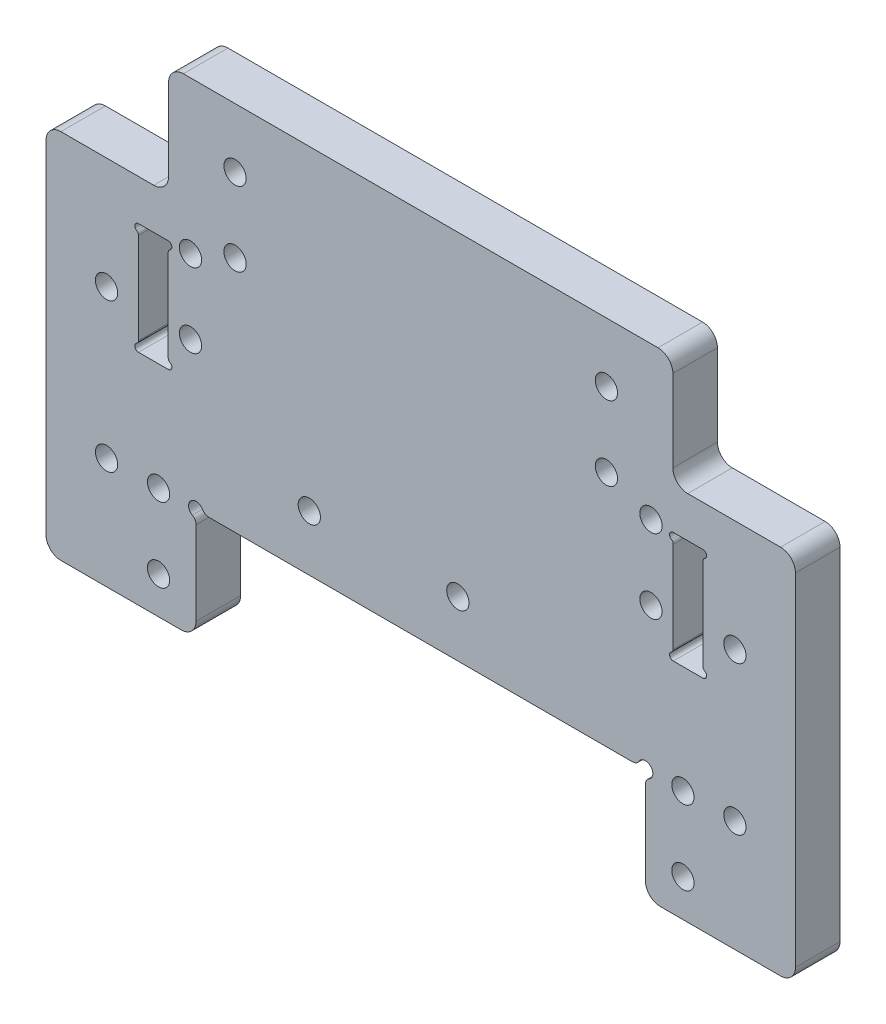
SolidWorks part; units mm, degrees
material "Thornel Mat VMA"
ref_plane "前视基准面" through (0, 0, 0) normal (0, 0, 1) x (1, 0, 0)
ref_plane "上视基准面" through (0, 0, 0) normal (0, 1, 0) x (1, 0, 0)
ref_plane "右视基准面" through (0, 0, 0) normal (1, 0, 0) x (0, 0, -1)
other "Configuration Table"
sketch "草图1" plane through (0, 0, 0) normal (0, 0, 1) x (1, 0, 0)
  line L0 (0, 0) -> (0, 15) construction
  line L1 (-35.3, -5) -> (35.3, -5) construction
  line L2 (-35.3, -5) -> (-35.3, 5) construction
  line L3 (-35.3, 5) -> (35.3, 5) construction
  line L4 (35.3, -5) -> (35.3, 5) construction
  line L5 (-35.3, -5) -> (35.3, 5) construction
  line L6 (-35.3, 5) -> (35.3, -5) construction
  line L7 (-42.3, 25) -> (-42.3, 5) construction
  line L8 (-42.3, 25) -> (42.3, 25) construction
  line L9 (-42.3, 25) -> (-42.3, 5) construction
  line L10 (-42.3, 5) -> (42.3, 5) construction
  line L11 (42.3, 25) -> (42.3, 5) construction
  line L12 (-42.3, 25) -> (42.3, 5) construction
  line L13 (-42.3, 5) -> (42.3, 25) construction
  line L14 (-35.3, -5) -> (-35.3, 5) construction
  line L16 (-50.45, 30) -> (50.45, 30)
  line L17 (-50.45, 30) -> (-50.45, -10)
  line L18 (-50.45, -10) -> (50.45, -10)
  line L19 (50.45, 30) -> (50.45, -10)
  line L20 (-50.45, 30) -> (50.45, -10) construction
  line L21 (-50.45, -10) -> (50.45, 30) construction
  circle A0 centre (42.3, 25) radius 1.5
  circle A1 centre (42.3, 5) radius 1.5
  circle A2 centre (35.3, 5) radius 1.5
  circle A3 centre (35.3, -5) radius 1.5
  circle A4 centre (-35.3, -5) radius 1.5
  circle A5 centre (-35.3, 5) radius 1.5
  circle A6 centre (-42.3, 5) radius 1.5
  circle A7 centre (-42.3, 25) radius 1.5
  point P0 (0, 0)
  point P20 (0, 10)
  dimension "D6" = 15
  dimension "D7" = 3
  dimension "D1" = 10
  dimension "D2" = 20
  dimension "D3" = 70.6
  dimension "D4" = 84.6
  dimension "D5" = 5
  dimension "D8" = 100.9
  dimension "D9" = 10
extrude "凸台-拉伸1" add sketch "草图1" along normal blind 6
sketch "草图6" plane through (0, 0, 6) normal (0, 0, 1) x (1, 0, 0)
  line L0 (0, 0) -> (0, 35) construction
  line L2 (-50.45, 40) -> (50.45, 40)
  line L3 (-50.45, 40) -> (-50.45, 30)
  line L4 (-50.45, 30) -> (50.45, 30)
  line L5 (50.45, 40) -> (50.45, 30)
  line L6 (-50.45, 40) -> (50.45, 30) construction
  line L7 (-50.45, 30) -> (50.45, 40) construction
  dimension "D1" = 10
extrude "凸台-拉伸2" add sketch "草图6" against normal up to surface (6 mm away) up to face at (0, 10, 0)
sketch "草图2" plane through (0, 0, 6) normal (0, 0, 1) x (1, 0, 0)
  line L0 (0, 0) -> (0, -2.5) construction
  line L1 (-50.45, -10) -> (50.45, -10) construction
  line L2 (-30.25, 5) -> (30.25, 5)
  line L3 (-30.25, 5) -> (-30.25, -10)
  line L4 (-30.25, -10) -> (30.25, -10)
  line L5 (30.25, 5) -> (30.25, -10)
  line L6 (-30.25, 5) -> (30.25, -10) construction
  line L7 (-30.25, -10) -> (30.25, 5) construction
  dimension "D1" = 60.5
  dimension "D2" = 15
extrude "切除-拉伸1" cut sketch "草图2" against normal blind 10
sketch "草图3" plane through (0, 0, 6) normal (0, 0, 1) x (1, 0, 0)
  circle A0 centre (-30.25, 5) radius 1
  circle A1 centre (30.25, 5) radius 1
  dimension "D1" = 2
extrude "切除-拉伸2" cut sketch "草图3" against normal blind 10
sketch "草图4" plane through (0, 0, 6) normal (0, 0, 1) x (1, 0, 0)
  line L0 (0, 0) -> (0, 29.5) construction
  line L2 (-31, 34.5) -> (31, 34.5) construction
  line L3 (-31, 34.5) -> (-31, 24.5) construction
  line L4 (-31, 24.5) -> (31, 24.5) construction
  line L5 (31, 34.5) -> (31, 24.5) construction
  line L6 (-31, 34.5) -> (31, 24.5) construction
  line L7 (-31, 24.5) -> (31, 34.5) construction
  circle A0 centre (31, 34.5) radius 1.5
  circle A1 centre (31, 24.5) radius 1.5
  circle A2 centre (-31, 24.5) radius 1.5
  circle A3 centre (-31, 34.5) radius 1.5
  dimension "D2" = 3
  dimension "D1" = 10
  dimension "D3" = 62
  dimension "D4" = 29.5
extrude "切除-拉伸3" cut sketch "草图4" against normal blind 10
sketch "草图5" plane through (0, 0, 6) normal (0, 0, 1) x (1, 0, 0)
  line L0 (0, 0) -> (0, 12.5) construction
  line L1 (0, 12.5) -> (-15, 12.5) construction
  line L2 (29.25, 5) -> (-29.25, 5) construction
  line L3 (0, 12.5) -> (5, 12.5) construction
  circle A0 centre (-15, 12.5) radius 1.5
  circle A2 centre (5, 12.5) radius 1.5
  dimension "D1" = 3
  dimension "D4" = 5
  dimension "D2" = 15
  dimension "D3" = 7.5
extrude "切除-拉伸4" cut sketch "草图5" against normal blind 10
sketch "草图7" plane through (0, 0, 6) normal (0, 0, 1) x (1, 0, 0)
  line L0 (0, 0) -> (0, 27) construction
  line L1 (0, 27) -> (36, 27) construction
  line L2 (50.45, 40) -> (-50.45, 40) construction
  line L3 (34, 19.5) -> (38, 19.5)
  line L4 (34, 19.5) -> (34, 34.5)
  line L5 (34, 34.5) -> (38, 34.5)
  line L6 (38, 19.5) -> (38, 34.5)
  line L7 (34, 19.5) -> (38, 34.5) construction
  line L8 (34, 34.5) -> (38, 19.5) construction
  line L10 (-34, 34.5) -> (-38, 19.5) construction
  line L11 (-34, 19.5) -> (-38, 34.5) construction
  line L12 (-38, 19.5) -> (-38, 34.5)
  line L13 (-34, 34.5) -> (-38, 34.5)
  line L14 (-34, 19.5) -> (-34, 34.5)
  line L15 (-34, 19.5) -> (-38, 19.5)
  circle A0 centre (31, 24.5) radius 1.5 construction
  dimension "D1" = 3
  dimension "D2" = 4
  dimension "D3" = 5.5
  dimension "D4" = 15
extrude "切除-拉伸5" cut sketch "草图7" against normal up to surface (6 mm away) up to face at (-13.5, 12.5, 0)
sketch "草图8" plane through (0, 0, 6) normal (0, 0, 1) x (1, 0, 0)
  line L0 (0, 0) -> (0, 45.2121) construction
  line L1 (-34, 19.5) -> (-34, 34.5) construction
  line L2 (-38, 34.5) -> (-38, 19.5) construction
  line L3 (-38, 34.5) -> (-38, 19.5)
  line L4 (-34, 19.5) -> (-34, 34.5)
  line L5 (34, 19.5) -> (34, 34.5)
  line L6 (38, 34.5) -> (38, 19.5)
  arc A0 (-34, 34.5) -> (-34, 33.5) centre (-34, 34) cw
  arc A1 (-38, 34.5) -> (-38, 33.5) centre (-38, 34) ccw
  arc A2 (-38, 19.5) -> (-38, 20.5) centre (-38, 20) cw
  arc A3 (-34, 19.5) -> (-34, 20.5) centre (-34, 20) ccw
  arc A4 (34, 19.5) -> (34, 20.5) centre (34, 20) cw
  arc A5 (38, 19.5) -> (38, 20.5) centre (38, 20) ccw
  arc A6 (38, 34.5) -> (38, 33.5) centre (38, 34) cw
  arc A7 (34, 34.5) -> (34, 33.5) centre (34, 34) ccw
  line M1 (38, 34.5) -> (38, 19.5)
  line M3 (34, 19.5) -> (34, 34.5)
  line M5 (-34, 34.5) -> (-34, 19.5)
  line M7 (-38, 19.5) -> (-38, 34.5)
  dimension "D1" = 0.5
extrude "切除-拉伸6" cut sketch "草图8" against normal up to surface (6 mm away) contours L3 A1 | A0 M5 | A2 M7 | A3 M5 | A6 M1 | A7 M3 | A4 M3 | L6 A5 up to face at (36, 27, 0)
fillet "圆角1" radius 0.5 8 edges at (38, 20.5, 3) (34, 20.5, 3) (34, 33.5, 3) (38, 33.5, 3) (-38, 20.5, 3) (-38, 33.5, 3) (-34, 33.5, 3) (-34, 20.5, 3)
fillet "圆角2" radius 1 4 edges at (30.25, 4, 3) (29.25, 5, 3) (-30.25, 4, 3) (-29.25, 5, 3)
sketch "草图9" plane through (0, 0, 6) normal (0, 0, 1) x (1, 0, 0)
  line L0 (0, 47.5) -> (0, 0) construction
  line L1 (-50.45, 55) -> (50.45, 55)
  line L2 (-50.45, 55) -> (-50.45, 40)
  line L3 (-50.45, 40) -> (50.45, 40)
  line L4 (50.45, 55) -> (50.45, 40)
  line L5 (-50.45, 55) -> (50.45, 40) construction
  line L6 (-50.45, 40) -> (50.45, 55) construction
  point P0 (0, 47.5)
  dimension "D1" = 15
extrude "凸台-拉伸3" add sketch "草图9" against normal up to surface (6 mm away) up to face at (-36, 27, 0)
sketch "草图10" plane through (0, 0, 6) normal (0, 0, 1) x (1, 0, 0)
  line L0 (0, 0) -> (0, 57.8919) construction
  line L1 (-33.95, 55) -> (-33.95, 40)
  line L2 (50.45, 55) -> (33.95, 55)
  line L3 (50.45, 55) -> (50.45, 40)
  line L4 (50.45, 40) -> (33.95, 40)
  line L5 (33.95, 55) -> (33.95, 40)
  line L6 (-50.45, 40) -> (-33.95, 40)
  line L7 (-50.45, 55) -> (-50.45, 40)
  line L8 (-50.45, 55) -> (-33.95, 55)
  dimension "D1" = 15
  dimension "D2" = 16.5
extrude "切除-拉伸7" cut sketch "草图10" against normal up to surface (6 mm away) up to face at (-36, 27, 0)
sketch "草图11" plane through (0, 0, 6) normal (0, 0, 1) x (1, 0, 0)
  line L0 (-33.95, 40) -> (-33.95, 55) construction
  line L1 (-33.95, 40) -> (-27.95, 40)
  line L2 (-33.95, 40) -> (-33.95, 55)
  line L3 (-33.95, 55) -> (-27.95, 55)
  line L4 (-27.95, 40) -> (-27.95, 55)
  line L5 (33.95, 55) -> (-33.95, 55) construction
  line L6 (-50.45, 40) -> (-33.95, 40) construction
  line L7 (33.95, 40) -> (27.95, 40)
  line L8 (33.95, 40) -> (33.95, 55)
  line L9 (33.95, 55) -> (27.95, 55)
  line L10 (27.95, 40) -> (27.95, 55)
  dimension "D1" = 6
extrude "凸台-拉伸4" add sketch "草图11" along normal blind 20 separate body contours L10 L7 L8 L9
sketch "草图12" plane through (33.95, 0, 0) normal (1, 0, 0) x (0, 0, -1)
  line L0 (-26, 40) -> (-26, 55) construction
  line L1 (-26, 55) -> (-6, 55) construction
  circle A0 centre (-21, 46.5) radius 2.5
  dimension "D1" = 5
  dimension "D2" = 5
  dimension "D3" = 8.5
extrude "切除-拉伸8" cut sketch "草图12" against normal up to surface (6 mm away) up to face at (27.95, 47.5, 16)
sketch "草图13" plane through (0, 0, 6) normal (0, 0, 1) x (1, 0, 0)
  line L0 (-25, 55) -> (-25, 47) construction
  line L1 (33.95, 55) -> (-33.95, 55) construction
  line L2 (-25, 47) -> (-25, 37) construction
  line L3 (-31, 24.5) -> (-31, 34.5) construction
  line L4 (0, 0) -> (0, 67.0246) construction
  line L5 (31, 24.5) -> (31, 34.5) construction
  line L6 (25, 47) -> (25, 37) construction
  line L7 (25, 55) -> (25, 47) construction
  circle A0 centre (-25, 47) radius 1.5
  circle A1 centre (-25, 37) radius 1.5
  circle A2 centre (25, 37) radius 1.5
  circle A3 centre (25, 47) radius 1.5
  dimension "D1" = 3
  dimension "D2" = 10
  dimension "D3" = 8
  dimension "D4" = 6
extrude "切除-拉伸9" cut sketch "草图13" against normal up to surface (6 mm away) up to face at (-36, 27, 0)
sketch "草图14" plane through (33.95, 0, 0) normal (1, 0, 0) x (0, 0, -1)
  line L0 (-9, 55) -> (-9, 52) construction
  line L1 (-26, 55) -> (-6, 55) construction
  line L2 (-9, 52) -> (-9, 42) construction
  line L3 (-6, 55) -> (-6, 40) construction
  circle A0 centre (-9, 42) radius 1.5
  circle A1 centre (-9, 52) radius 1.5
  dimension "D4" = 3
  dimension "D1" = 3
  dimension "D2" = 3
  dimension "D3" = 10
extrude "切除-拉伸10" cut sketch "草图14" against normal up to surface (6 mm away) up to face at (27.95, 46.5, 23.5)
sketch "草图15" plane through (33.95, 0, 0) normal (1, 0, 0) x (0, 0, -1)
  line L0 (-26, 40) -> (-26, 55) construction
  line L1 (-6, 40) -> (-26, 40)
  line L2 (-6, 40) -> (-6, 38)
  line L3 (-6, 38) -> (-26, 38)
  line L4 (-26, 40) -> (-26, 38)
  dimension "D1" = 2
extrude "凸台-拉伸5" add sketch "草图15" against normal blind 6
fillet "圆角4" radius 2 2 edges at (30.95, 55, 26) (30.95, 38, 26)
fillet "圆角5" radius 2 10 edges at (50.45, 40, 3) (50.45, -10, 3) (30.25, -10, 3) (-30.25, -10, 3) (-50.45, 40, 3) (-33.95, 40, 3) (-33.95, 55, 3) (33.95, 55, 3) (33.95, 40, 3) (-50.45, -10, 3)
mirror "镜向1" about plane through (0, 0, 0) normal (1, 0, 0) of bodies 120
sketch "草图19" plane through (-27.95, 0, 0) normal (1, 0, 0) x (0, 0, -1)
  circle A0 centre (-21, 46.5) radius 4.5
  circle A1 centre (-21, 46.5) radius 2.5
  dimension "D1" = 9
  dimension "D2" = 5
extrude "凸台-拉伸6" add sketch "草图19" along normal up to surface (55.9 mm away) separate body up to face at (27.95, 42, 10.5)
delete or keep bodies "实体-删除/保留 1" type delete bodies bodies 120 122 121
